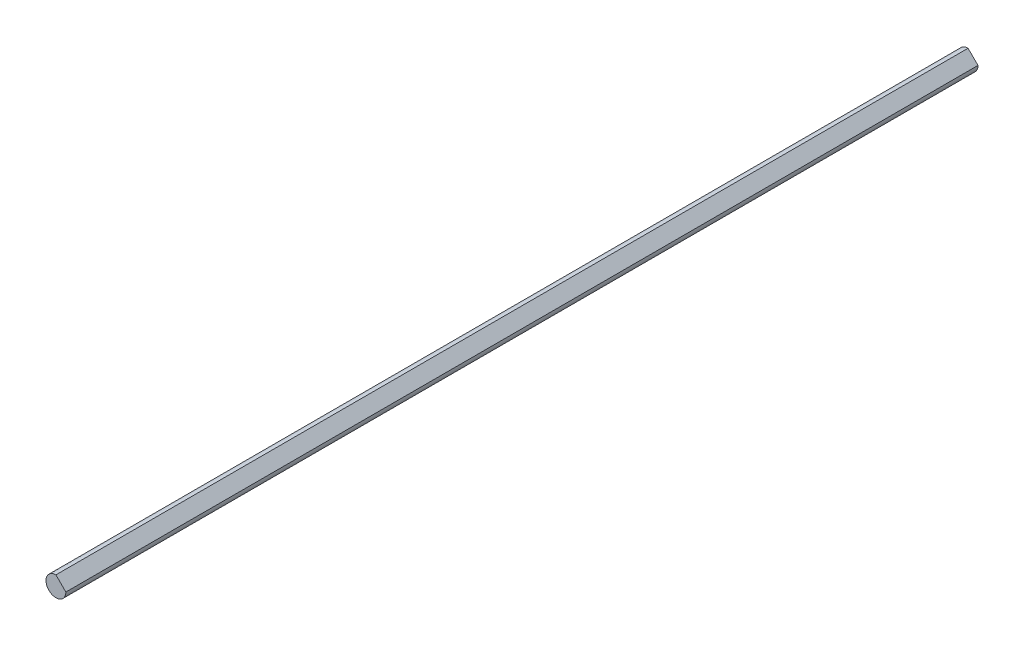
SolidWorks part; units mm, degrees
ref_plane "Front Plane" through (0, 0, 0) normal (0, 0, 1) x (1, 0, 0)
ref_plane "Top Plane" through (0, 0, 0) normal (0, 1, 0) x (1, 0, 0)
ref_plane "Right Plane" through (0, 0, 0) normal (1, 0, 0) x (0, 0, -1)
sketch "Sketch1" plane through (0, 0, 0) normal (0, 0, 1) x (1, 0, 0)
  line L0 (0, 3.81) -> (3.81, 0)
  arc A0 (0, 3.81) -> (3.81, 0) centre (0, 0) ccw
  dimension "D1" = 7.62
extrude "Boss-Extrude1" add sketch "Sketch1" along normal blind 350
